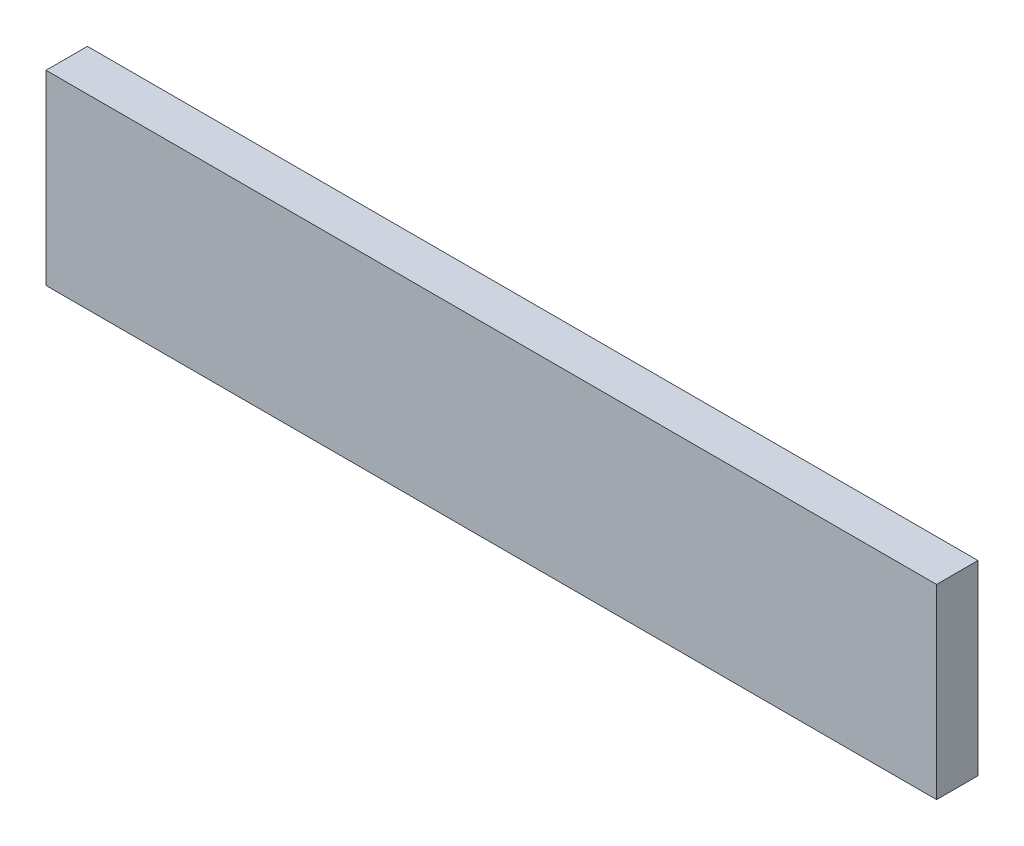
SolidWorks part; units mm, degrees
ref_plane "前视基准面" through (0, 0, 0) normal (0, 0, 1) x (1, 0, 0)
ref_plane "上视基准面" through (0, 0, 0) normal (0, 1, 0) x (1, 0, 0)
ref_plane "右视基准面" through (0, 0, 0) normal (1, 0, 0) x (0, 0, -1)
other "Configuration Table"
sketch "草图1" plane through (0, 0, 0) normal (0, 0, 1) x (1, 0, 0)
  line L0 (0, 0) -> (86, 0)
  line L1 (86, 0) -> (86, 18)
  line L2 (86, 18) -> (0, 18)
  line L3 (0, 18) -> (0, 0)
  dimension "width" = 86
  dimension "height" = 18
extrude "Pitch_Yoke_Beam" add sketch "草图1" along normal blind 4
